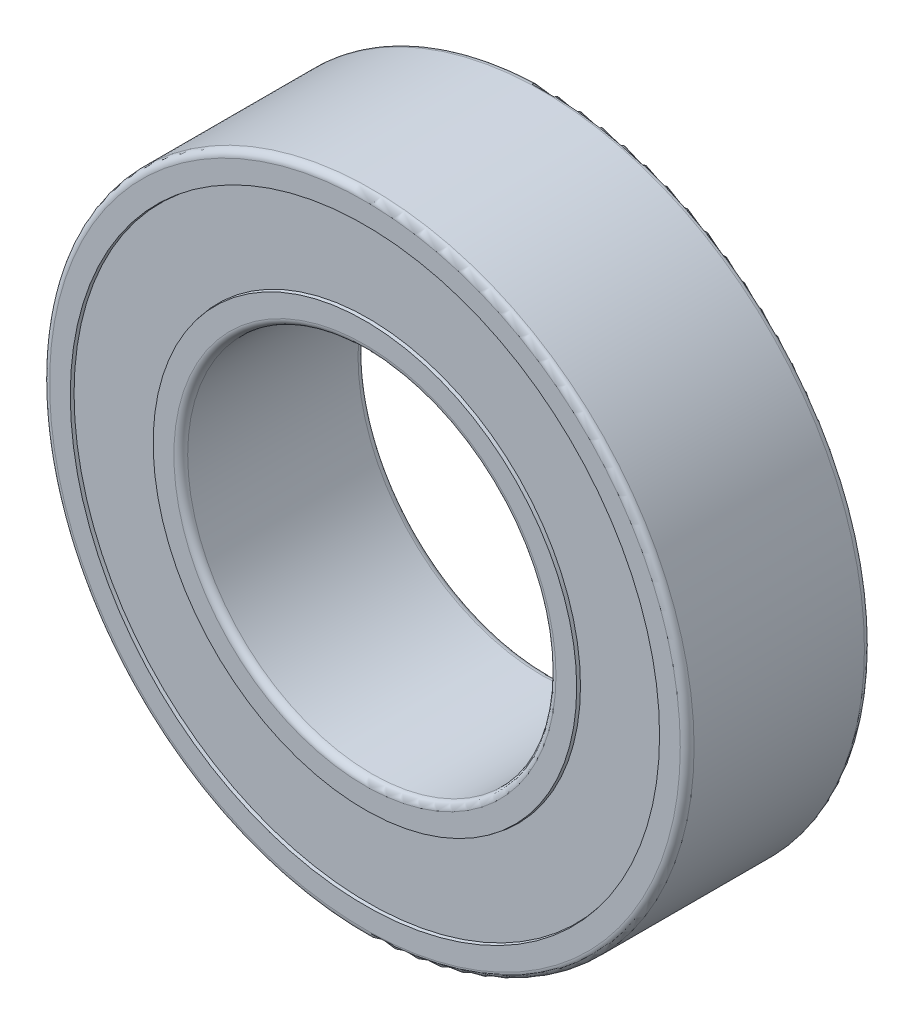
SolidWorks part; units mm, degrees
material "AISI 1010 Steel, hot rolled bar"
ref_plane "Front" through (0, 0, 0) normal (0, 0, 1) x (1, 0, 0)
ref_plane "Top" through (0, 0, 0) normal (0, 1, 0) x (1, 0, 0)
ref_plane "Right" through (0, 0, 0) normal (1, 0, 0) x (0, 0, -1)
sketch "Sketch1" plane through (0, 0, 0) normal (1, 0, 0) x (0, 0, -1)
  line L0 (0, 0) -> (5.8679, 0) construction
  line L1 (-1.85, 7) -> (1.85, 7)
  line L2 (2, 6.85) -> (2, 6.4)
  line L3 (2, 6.4) -> (1.93, 6.3877)
  line L4 (1.93, 6.3877) -> (1.93, 4.6123)
  line L5 (1.93, 4.6123) -> (2, 4.6)
  line L6 (2, 4.6) -> (2, 4.15)
  line L7 (1.85, 4) -> (-1.85, 4)
  line L8 (-2, 4.6) -> (-2, 4.15)
  line L9 (-1.93, 4.6123) -> (-2, 4.6)
  line L10 (-1.93, 6.3877) -> (-1.93, 4.6123)
  line L11 (-2, 6.4) -> (-1.93, 6.3877)
  line L12 (-2, 6.85) -> (-2, 6.4)
  line L13 (0, 0) -> (0, 7) construction
  line L14 (0, 5.5) -> (2.8598, 5.5) construction
  arc A0 (-1.85, 7) -> (-2, 6.85) centre (-1.85, 6.85) ccw
  arc A1 (1.85, 7) -> (2, 6.85) centre (1.85, 6.85) cw
  arc A2 (2, 4.15) -> (1.85, 4) centre (1.85, 4.15) cw
  arc A3 (-2, 4.15) -> (-1.85, 4) centre (-1.85, 4.15) ccw
  point P20 (-2, 7)
  point P23 (2, 7)
  point P26 (2, 4)
  point P29 (-2, 4)
  dimension "D5" = 0.15
  dimension "D6" = 0.07
  dimension "D1" = 4
  dimension "D2" = 8
  dimension "D3" = 14
  dimension "D4" = 12.8
  dimension "D7" = 10
revolve "Revolve1" add sketch "Sketch1" angle 360 about L0
